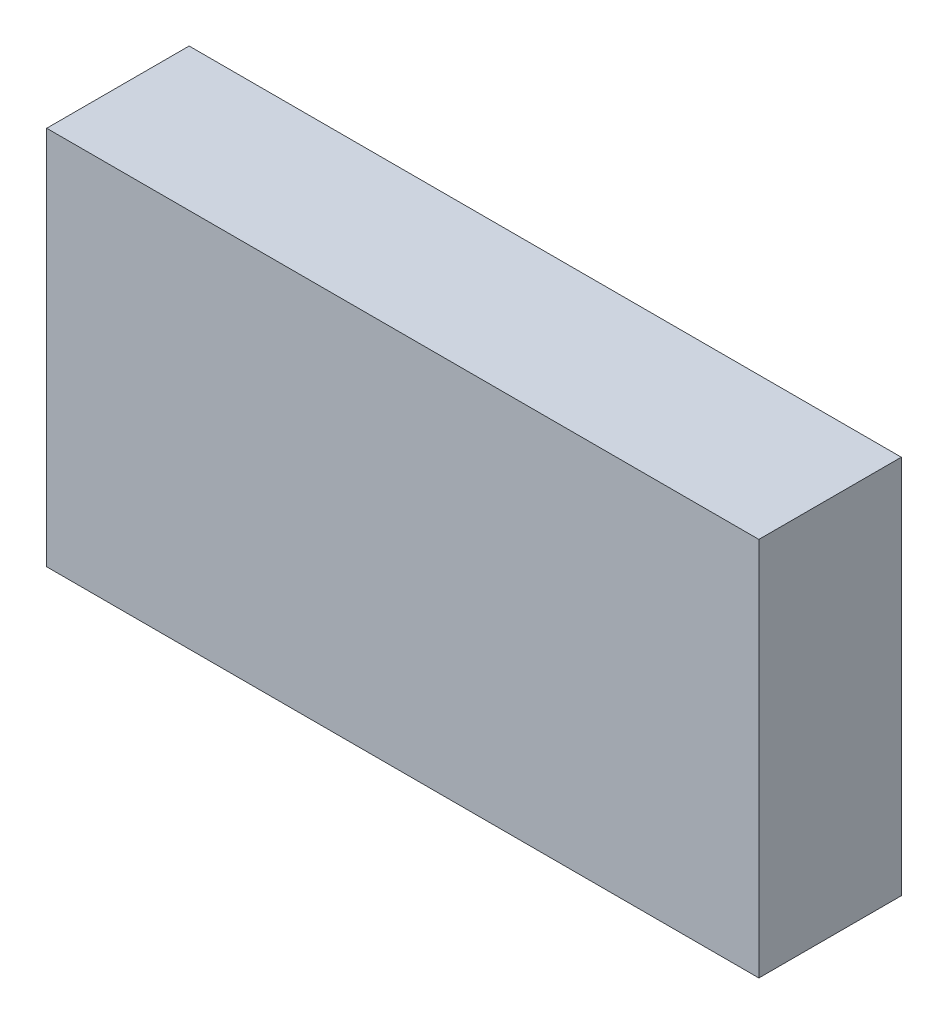
SolidWorks part; units mm, degrees
ref_plane "Front Plane" through (0, 0, 0) normal (0, 0, 1) x (1, 0, 0)
ref_plane "Top Plane" through (0, 0, 0) normal (0, 1, 0) x (1, 0, 0)
ref_plane "Right Plane" through (0, 0, 0) normal (1, 0, 0) x (0, 0, -1)
other "Configuration Table"
sketch "Sketch1" plane through (0, 0, 0) normal (0, 0, 1) x (1, 0, 0)
  line L1 (596, 98) -> (611, 98)
  line L2 (596, 98) -> (596, 106)
  line L3 (596, 106) -> (611, 106)
  line L4 (611, 98) -> (611, 106)
extrude "CEK_icecek_miknatis_15x8x3_1" add sketch "Sketch1" against normal blind 3 separate body
